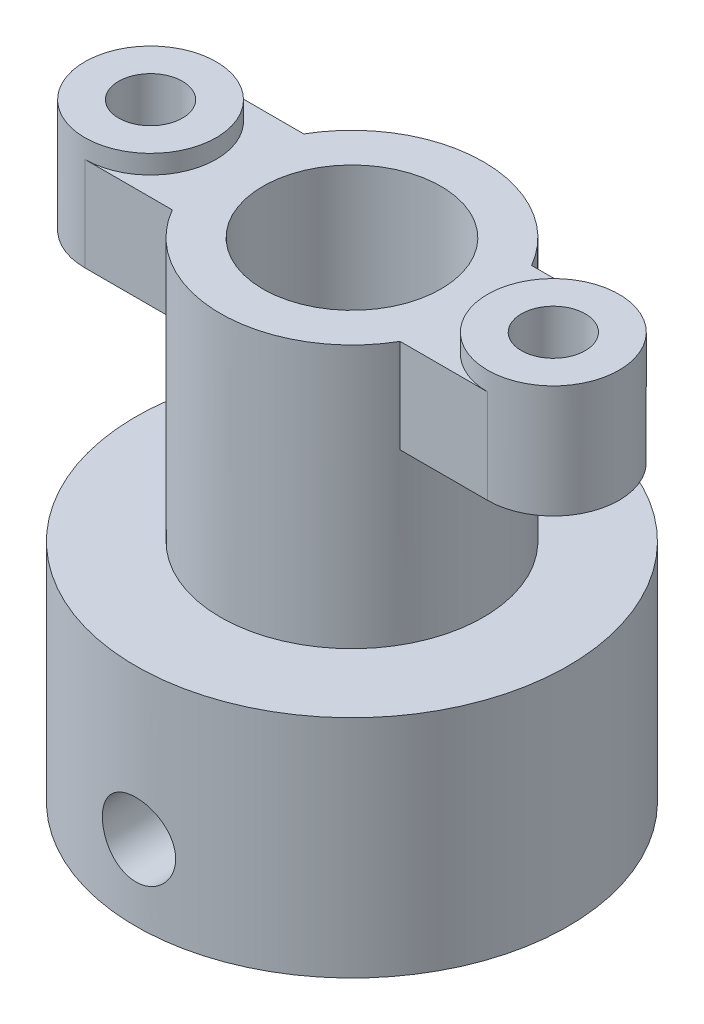
SolidWorks part; units mm, degrees
ref_plane "Plan de face" through (0, 0, 0) normal (0, 0, 1) x (1, 0, 0)
ref_plane "Plan de dessus" through (0, 0, 0) normal (0, 1, 0) x (1, 0, 0)
ref_plane "Plan de droite" through (0, 0, 0) normal (1, 0, 0) x (0, 0, -1)
sketch "Esquisse1" plane through (0, 0, 0) normal (0, 1, 0) x (1, 0, 0)
  line L0 (-10.72, 3.5) -> (-6.0622, 3.5)
  line L1 (-10.72, -3.5) -> (-6.0622, -3.5)
  line L2 (10.72, 3.5) -> (6.0622, 3.5)
  line L4 (10.72, -3.5) -> (6.0622, -3.5)
  arc A1 (6.0622, 3.5) -> (-6.0622, 3.5) centre (0, 0) ccw
  circle A2 centre (10.72, 0) radius 1.7
  circle A3 centre (-10.72, 0) radius 1.7
  arc A4 (-10.72, 3.5) -> (-10.72, -3.5) centre (-10.72, 0) ccw
  arc A5 (10.72, -3.5) -> (10.72, 3.5) centre (10.72, 0) ccw
  arc A7 (-6.0622, -3.5) -> (6.0622, -3.5) centre (0, 0) ccw
  dimension "D1" = 14
  dimension "D5" = 3.4
  dimension "D6" = 3.4
  dimension "D7" = 7
  dimension "D8" = 7
  dimension "D3" = 10.72
  dimension "D4" = 10.72
  dimension "D9" = 0
extrude "Boss.-Extru.1" add sketch "Esquisse1" along normal blind 5
sketch "Esquisse2" plane through (0, 5, 0) normal (0, 1, 0) x (1, 0, 0)
  circle A0 centre (-10.72, 0) radius 3.5
  circle A1 centre (-10.72, 0) radius 1.7
  circle A2 centre (10.72, 0) radius 1.7
  circle A3 centre (10.72, 0) radius 3.5
  circle A4 centre (-10.72, 0) radius 1.7 construction
  circle A5 centre (10.72, 0) radius 1.7 construction
extrude "Boss.-Extru.2" add sketch "Esquisse2" along normal blind 1
sketch "Esquisse5" plane through (0, 0, 0) normal (0, -1, 0) x (1, 0, 0)
  circle A0 centre (0, 0) radius 7
extrude "Boss.-Extru.3" add sketch "Esquisse5" along normal blind 9
sketch "Esquisse6" plane through (0, -9, 0) normal (0, -1, 0) x (1, 0, 0)
  circle A0 centre (0, 0) radius 11.5
  point P14 (0, 0)
  dimension "D1" = 23
extrude "Boss.-Extru.4" add sketch "Esquisse6" along normal blind 2
sketch "Esquisse7" plane through (0, 5, 0) normal (0, 1, 0) x (1, 0, 0)
  circle A0 centre (0, 0) radius 4.7398
extrude "Enlèv. mat.-Extru.1" cut sketch "Esquisse7" against normal blind 10
sketch "Esquisse8" plane through (0, -11, 0) normal (0, -1, 0) x (1, 0, 0)
  circle A0 centre (0, 0) radius 11.5
  circle A1 centre (0, 0) radius 6.75
extrude "Boss.-Extru.5" add sketch "Esquisse8" along normal blind 10
sketch "Esquisse10" plane through (0, -11, 0) normal (0, -1, 0) x (1, 0, 0)
  circle A0 centre (0, 0) radius 6.2
  circle A1 centre (0, 0) radius 6.9395
  dimension "D1" = 12.4
extrude "Boss.-Extru.6" add sketch "Esquisse10" along normal up to surface (10 mm away) up to face at (0, -21, -11.5)
sketch "Esquisse9" plane through (0, 0, 0) normal (0, 0, 1) x (1, 0, 0)
  line L0 (-11.5, -21) -> (11.5, -21) construction
  circle A0 centre (0, -17) radius 1.95
  dimension "D1" = 3.9
  dimension "D2" = 4
extrude "Enlèv. mat.-Extru.2" cut sketch "Esquisse9" against normal through all both and the other way through all
sketch "Esquisse11" plane through (0, -11, 0) normal (0, -1, 0) x (1, 0, 0)
  line L0 (0, 6.2) -> (6.2, 0)
  circle A0 centre (0, 0) radius 3.9 construction
  arc A1 (6.2, 0) -> (0, 6.2) centre (0, 0) ccw
  circle A2 centre (0, 0) radius 6.2 construction
  circle A3 centre (0, 0) radius 6.2 construction
  dimension "D1" = 7.8
extrude "Boss.-Extru.7" add sketch "Esquisse11" along normal blind 4
sketch "Esquisse12" plane through (0, -21, 0) normal (0, -1, 0) x (1, 0, 0)
  circle A0 centre (0, 0) radius 9
  dimension "D1" = 18
extrude "Enlèv. mat.-Extru.3" cut sketch "Esquisse12" against normal blind 2
